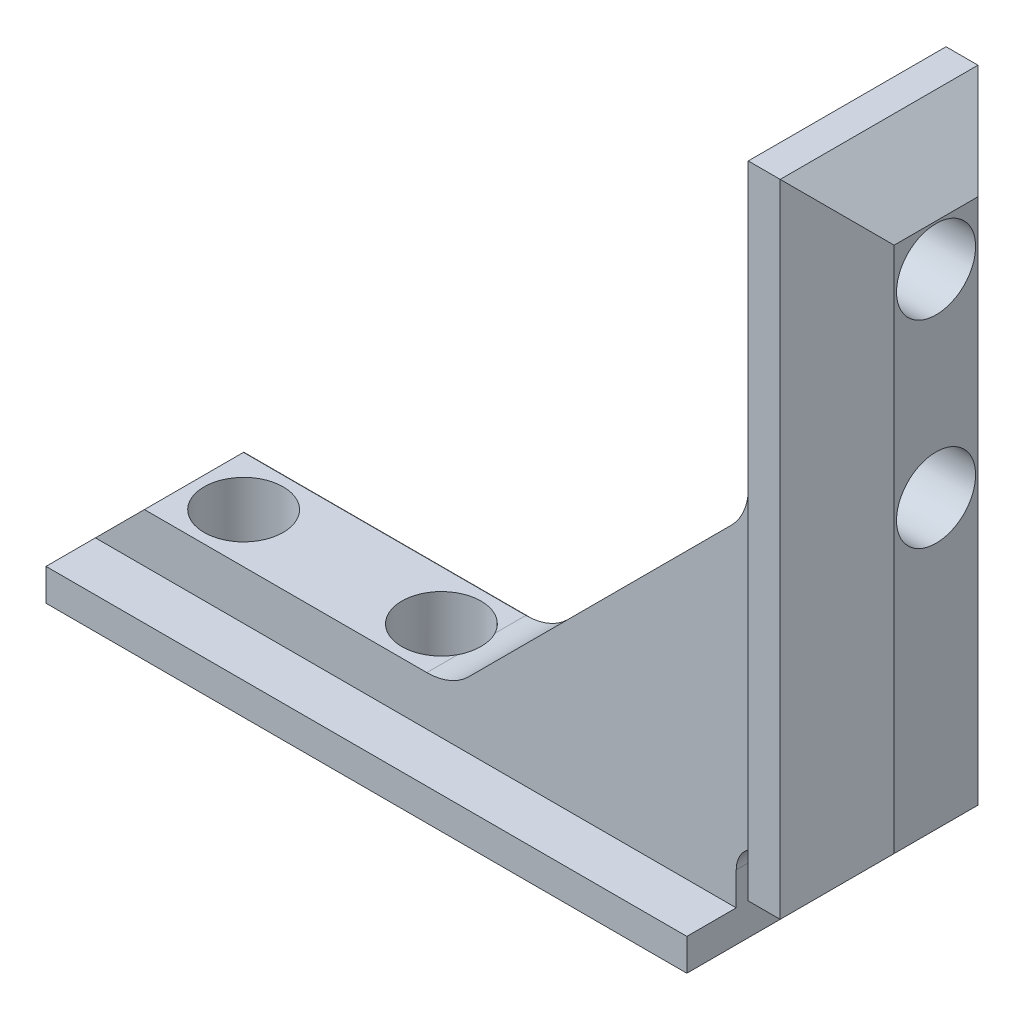
SolidWorks part; units mm, degrees
material "1060 Alloy"
ref_plane "Front Plane" through (0, 0, 0) normal (0, 0, 1) x (1, 0, 0)
ref_plane "Top Plane" through (0, 0, 0) normal (0, 1, 0) x (1, 0, 0)
ref_plane "Right Plane" through (0, 0, 0) normal (1, 0, 0) x (0, 0, -1)
sketch "Sketch1" plane through (0, 0, 0) normal (0, 0, 1) x (1, 0, 0)
  line L0 (108.5797, 130.4089) -> (87.5189, 109.3481)
  line L1 (109.9746, 156.4418) -> (109.9746, 133.7765)
  line L2 (113.9116, 160.3788) -> (109.9746, 156.4418)
  line L3 (116.477, 160.3788) -> (113.9116, 160.3788)
  line L4 (121.049, 155.8068) -> (116.477, 160.3788)
  line L5 (121.049, 155.8068) -> (121.049, 113.5158)
  line L6 (116.477, 108.9438) -> (121.049, 113.5158)
  line L7 (111.27, 108.9438) -> (116.477, 108.9438)
  line L8 (108.984, 101.4508) -> (108.984, 106.6578)
  line L9 (104.412, 96.8788) -> (108.984, 101.4508)
  line L10 (62.121, 96.8788) -> (104.412, 96.8788)
  line L11 (57.549, 101.4508) -> (62.121, 96.8788)
  line L12 (57.549, 104.0162) -> (57.549, 101.4508)
  line L13 (61.486, 107.9532) -> (57.549, 104.0162)
  line L14 (84.1513, 107.9532) -> (61.486, 107.9532)
  arc A0 (108.5797, 130.4089) -> (109.9746, 133.7765) centre (105.2121, 133.7765) ccw
  arc A1 (111.27, 108.9438) -> (108.984, 106.6578) centre (111.27, 106.6578) ccw
  arc A2 (84.1513, 107.9532) -> (87.5189, 109.3481) centre (84.1513, 112.7157) ccw
extrude "Extrude1" add sketch "Sketch1" along normal blind 15.875
sketch "Sketch2" plane through (0, 0, 15.875) normal (0, 0, 1) x (1, 0, 0)
  line L1 (57.549, 104.0162) -> (113.9116, 104.0162)
  line L2 (57.549, 104.0162) -> (57.549, 160.3788)
  line L3 (57.549, 160.3788) -> (113.9116, 160.3788)
  line L4 (113.9116, 104.0162) -> (113.9116, 160.3788)
extrude "Cut-Extrude1" cut sketch "Sketch2" against normal blind 3.9624
sketch "Sketch3" plane through (0, 0, 0) normal (0, 0, -1) x (-1, 0, 0)
  line L1 (-57.549, 104.0162) -> (-113.9116, 104.0162)
  line L2 (-57.549, 104.0162) -> (-57.549, 160.3788)
  line L3 (-57.549, 160.3788) -> (-113.9116, 160.3788)
  line L4 (-113.9116, 104.0162) -> (-113.9116, 160.3788)
extrude "Cut-Extrude2" cut sketch "Sketch3" against normal blind 3.9624
sketch "Sketch4" plane through (57.549, 0, 0) normal (-1, 0, 0) x (0, 0, 1)
  line L1 (0, 101.4508) -> (4.572, 96.8788)
  line L2 (4.572, 96.8788) -> (11.303, 96.8788)
  line L3 (15.875, 101.4508) -> (11.303, 96.8788)
  line L5 (0, 101.4508) -> (-3.5167, 97.8664)
  line L6 (-3.5167, 97.8664) -> (9.313, 92.3138)
  line L7 (9.313, 92.3138) -> (19.7121, 96.1408)
  line L8 (19.7121, 96.1408) -> (15.875, 101.4508)
extrude "Cut-Extrude3" cut sketch "Sketch4" against normal through all
sketch "Sketch6" plane through (0, 160.3788, 0) normal (0, 1, 0) x (1, 0, 0)
  line L1 (116.477, -15.875) -> (121.049, -11.303)
  line L2 (121.049, -11.303) -> (121.049, -4.572)
  line L3 (116.477, 0) -> (121.049, -4.572)
  line L5 (116.477, 0) -> (122.8518, 1.0258)
  line L6 (122.8518, 1.0258) -> (123.5958, -16.1922)
  line L7 (123.5958, -16.1922) -> (117.2541, -18.4596)
  line L8 (117.2541, -18.4596) -> (116.477, -15.875)
extrude "Cut-Extrude4" cut sketch "Sketch6" against normal through all
sketch "Sketch7" plane through (57.549, 0, 0) normal (-1, 0, 0) x (0, 0, 1)
  circle A0 centre (7.9375, 136.579) radius 3.175
  circle A1 centre (7.9375, 152.454) radius 3.175
extrude "Cut-Extrude6" cut sketch "Sketch7" against normal through all
sketch "Sketch9" plane through (0, 107.9532, 0) normal (0, 1, 0) x (1, 0, 0)
  circle A0 centre (65.4738, -7.9375) radius 3.175
  circle A1 centre (81.3488, -7.9375) radius 3.175
extrude "Cut-Extrude7" cut sketch "Sketch9" against normal through all and the other way blind 3.9624
